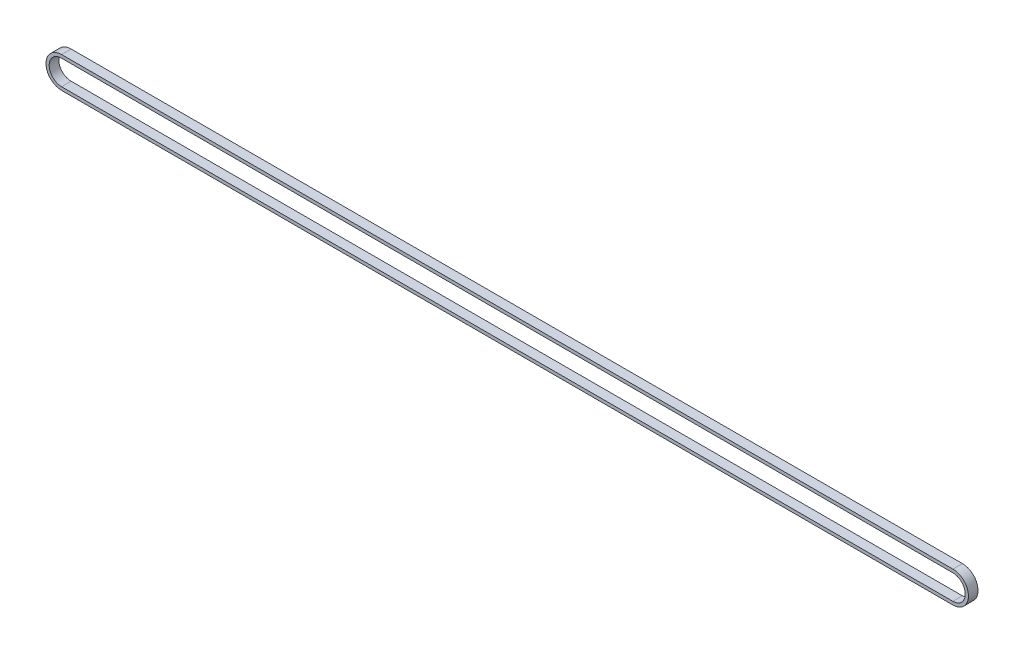
SolidWorks part; units mm, degrees
ref_plane "Front Plane" through (0, 0, 0) normal (0, 0, 1) x (1, 0, 0)
ref_plane "Top Plane" through (0, 0, 0) normal (0, 1, 0) x (1, 0, 0)
ref_plane "Right Plane" through (0, 0, 0) normal (1, 0, 0) x (0, 0, -1)
sketch "Sketch1" plane through (0, 0, 0) normal (0, 0, 1) x (1, 0, 0)
  line L0 (0, 0) -> (559, 0) construction
  line L1 (0, 7.75) -> (559, 7.75)
  line L2 (0, -7.75) -> (559, -7.75)
  line L3 (0, 9.75) -> (559, 9.75)
  line L4 (0, -9.75) -> (559, -9.75)
  arc A0 (0, 7.75) -> (0, -7.75) centre (0, 0) ccw
  arc A1 (559, -7.75) -> (559, 7.75) centre (559, 0) ccw
  arc A2 (559, -9.75) -> (559, 9.75) centre (559, 0) ccw
  arc A3 (0, 9.75) -> (0, -9.75) centre (0, 0) ccw
  point P3 (279.5, 0)
  dimension "D1" = 559
  dimension "D2" = 7.75
  dimension "D3" = 2
extrude "Boss-Extrude1" add sketch "Sketch1" along normal blind 6
